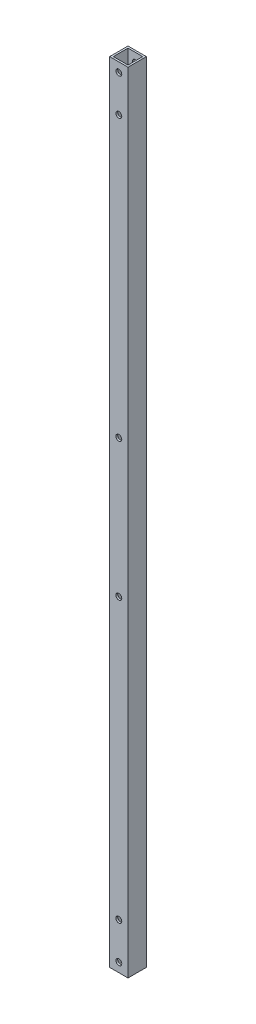
SolidWorks part; units mm, degrees
ref_plane "正面" through (0, 0, 0) normal (0, 0, 1) x (1, 0, 0)
ref_plane "平面" through (0, 0, 0) normal (0, 1, 0) x (1, 0, 0)
ref_plane "右側面" through (0, 0, 0) normal (1, 0, 0) x (0, 0, -1)
sketch "ｽｹｯﾁ1" plane through (0, 0, 0) normal (0, 1, 0) x (1, 0, 0)
  line L0 (-4, 4) -> (4, 4)
  line L1 (-5, 5) -> (5, 5)
  line L2 (-5, 5) -> (-5, -5)
  line L3 (-5, -5) -> (5, -5)
  line L4 (5, 5) -> (5, -5)
  line L5 (-5, 5) -> (5, -5) construction
  line L6 (-5, -5) -> (5, 5) construction
  line L7 (4, 4) -> (4, -4)
  line L8 (-4, -4) -> (4, -4)
  line L9 (-4, 4) -> (-4, -4)
  point P0 (0, 0)
  dimension "D1" = 10
  dimension "D2" = 1
extrude "ﾎﾞｽ - 押し出し1" add sketch "ｽｹｯﾁ1" along normal mid plane 429.94
sketch "ｽｹｯﾁ2" plane through (0, 0, 5) normal (0, 0, 1) x (1, 0, 0)
  line L0 (0, 214.97) -> (0, 209.97) construction
  line L1 (-5, 214.97) -> (5, 214.97) construction
  line L2 (0, 209.97) -> (0, 189.97) construction
  circle A0 centre (0, 209.97) radius 1.6
  circle A1 centre (0, 189.97) radius 1.6
  dimension "D3" = 3.2
  dimension "D4" = 3.2
  dimension "D1" = 5
  dimension "D2" = 20
extrude "ｶｯﾄ - 押し出し1" cut sketch "ｽｹｯﾁ2" against normal mid plane 427.43
mirror "ﾐﾗｰ1" about plane through (0, 0, 0) normal (0, 1, 0) of "ｶｯﾄ - 押し出し1"
sketch "ｽｹｯﾁ3" plane through (0, 0, -5) normal (0, 0, -1) x (-1, 0, 0)
  line L0 (0, 0) -> (0, 37.5) construction
  line L1 (0, 37.5) -> (0, -37.5) construction
  circle A4 centre (0, 37.5) radius 1.6
  circle A5 centre (0, -37.5) radius 1.6
  dimension "D3" = 3.2
  dimension "D4" = 3.2
  dimension "D1" = 37.5
  dimension "D2" = 75
extrude "ｶｯﾄ - 押し出し2" cut sketch "ｽｹｯﾁ3" against normal blind 10
